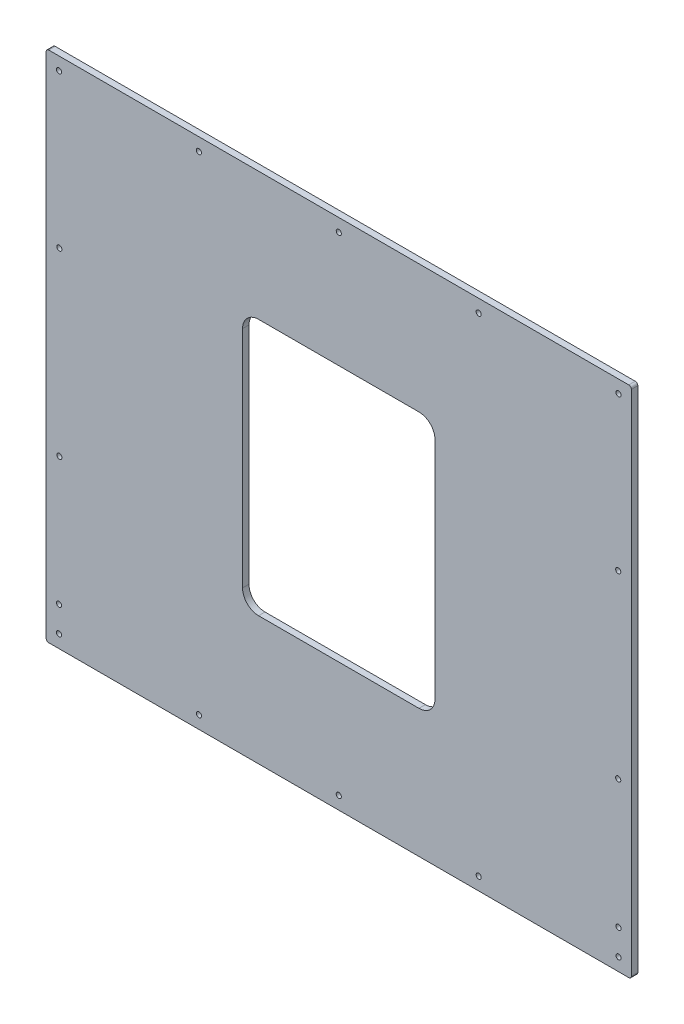
SolidWorks part; units mm, degrees
ref_plane "Plan de face" through (0, 0, 0) normal (0, 0, 1) x (1, 0, 0)
ref_plane "Plan de dessus" through (0, 0, 0) normal (0, 1, 0) x (1, 0, 0)
ref_plane "Plan de droite" through (0, 0, 0) normal (1, 0, 0) x (0, 0, -1)
sketch "Esquisse1" plane through (0, 0, 0) normal (0, 0, 1) x (1, 0, 0)
  line L1 (-452, -400) -> (452, -400)
  line L2 (-456, -396) -> (-456, 396)
  line L3 (-452, 400) -> (452, 400)
  line L4 (456, -396) -> (456, 396)
  line L5 (-456, -400) -> (456, 400) construction
  line L6 (-456, 400) -> (456, -400) construction
  line L7 (0, 400) -> (0, -400) construction
  line L8 (-456, 0) -> (456, 0) construction
  arc A0 (-456, 396) -> (-452, 400) centre (-452, 396) cw
  arc A1 (456, 396) -> (452, 400) centre (452, 396) ccw
  arc A2 (452, -400) -> (456, -396) centre (452, -396) ccw
  arc A3 (-456, -396) -> (-452, -400) centre (-452, -396) ccw
  circle A4 centre (436, 380) radius 4
  circle A5 centre (435.5, -140) radius 4
  circle A6 centre (435.5, 141) radius 4
  circle A7 centre (-435.5, -140) radius 4
  circle A8 centre (-436, 380) radius 4
  circle A9 centre (-435.5, 141) radius 4
  circle A10 centre (436, -380) radius 4
  circle A11 centre (436, -340) radius 4
  circle A12 centre (-436, -340) radius 4
  circle A13 centre (-436, -380) radius 4
  circle A14 centre (218, -380) radius 4
  circle A15 centre (0, -380) radius 4
  circle A16 centre (-218, -380) radius 4
  circle A17 centre (-218, 380) radius 4
  circle A18 centre (0, 380) radius 4
  circle A19 centre (218, 380) radius 4
  point P0 (0, 0)
  dimension "D3" = 4
  dimension "D4" = 4
  dimension "D5" = 4
  dimension "D6" = 4
  dimension "D7" = 8
  dimension "D8" = 20
  dimension "D9" = 20
  dimension "D11" = 20.5
  dimension "D12" = 259
  dimension "D13" = 8
  dimension "D14" = 2
  dimension "D1" = 912
  dimension "D2" = 800
  dimension "D15" = 4
  dimension "D10" = 2
extrude "Boss.-Extru.1" add sketch "Esquisse1" along normal blind 10
sketch "Esquisse2" plane through (0, 0, 10) normal (0, 0, 1) x (1, 0, 0)
  line L0 (-125, -200) -> (125, -200)
  line L1 (-150, -175) -> (-150, 175)
  line L2 (150, -175) -> (150, 175)
  line L3 (-125, 200) -> (125, 200)
  line L4 (-125, -175) -> (125, 175) construction
  arc A0 (-125, 200) -> (-150, 175) centre (-125, 175) ccw
  arc A1 (125, 200) -> (150, 175) centre (125, 175) cw
  arc A2 (150, -175) -> (125, -200) centre (125, -175) cw
  arc A3 (-150, -175) -> (-125, -200) centre (-125, -175) ccw
  point P9 (150, 200)
  point P12 (150, -200)
  dimension "D3" = 300
  dimension "D2" = 25
  dimension "D1" = 400
extrude "Enlèv. mat.-Extru.1" cut sketch "Esquisse2" against normal through all
